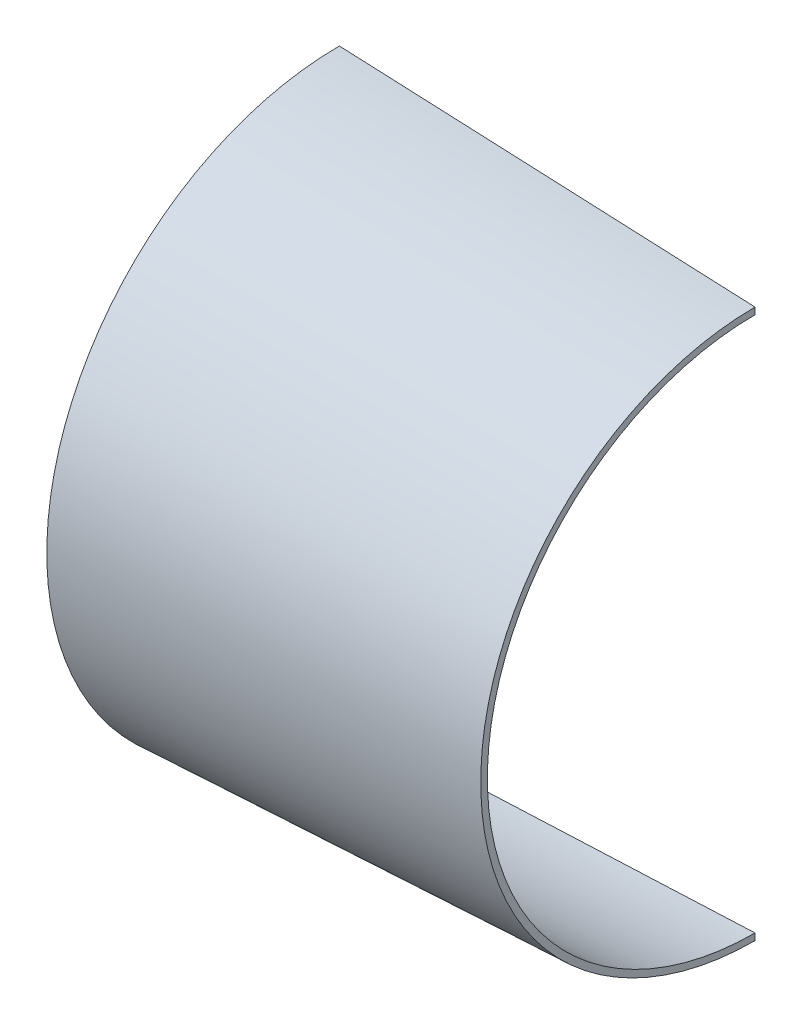
SolidWorks part; units mm, degrees
ref_plane "Front Plane" through (0, 0, 0) normal (0, 0, 1) x (1, 0, 0)
ref_plane "Top Plane" through (0, 0, 0) normal (0, 1, 0) x (1, 0, 0)
ref_plane "Right Plane" through (0, 0, 0) normal (1, 0, 0) x (0, 0, -1)
sketch "Sketch1" plane through (0, 0, 0) normal (0, 0, 1) x (1, 0, 0)
  line L0 (0, 0) -> (4000, 0) construction
  line L1 (700, 1720) -> (700, 1760)
  line L2 (700, 1760) -> (3200, 1650)
  line L3 (3200, 1650) -> (3200, 1610)
  line L4 (3200, 1610) -> (700, 1720)
revolve "Revolve1" add sketch "Sketch1" angle 180 about L0
